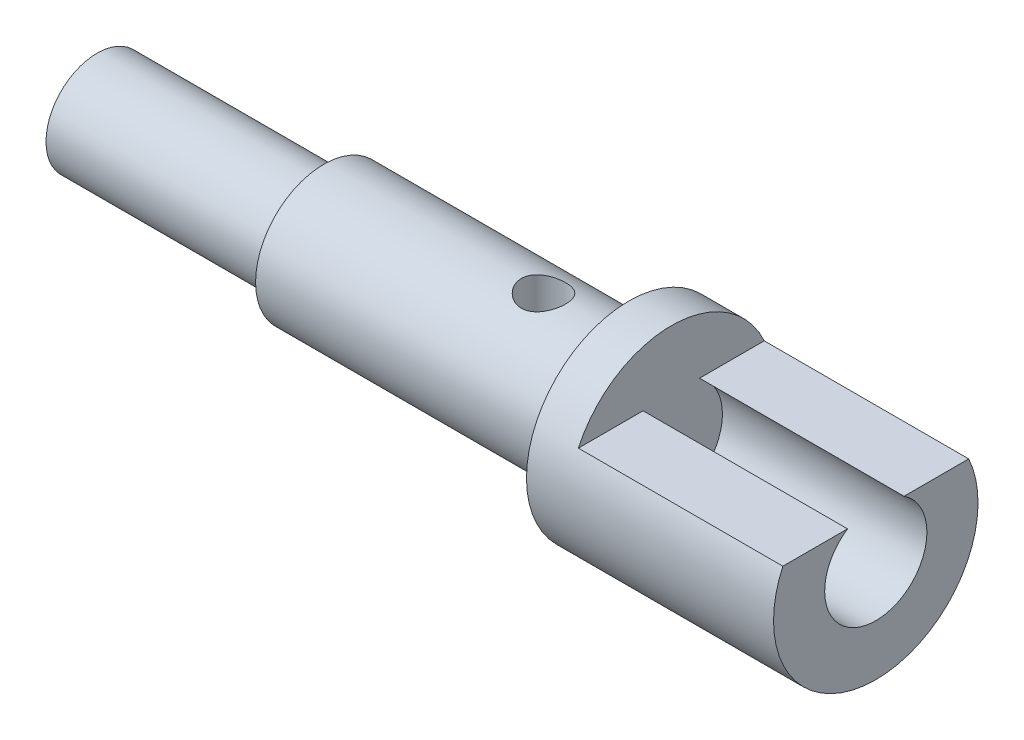
SolidWorks part; units mm, degrees
material "6063-O"
ref_plane "正面" through (0, 0, 0) normal (0, 0, 1) x (1, 0, 0)
ref_plane "平面" through (0, 0, 0) normal (0, 1, 0) x (1, 0, 0)
ref_plane "右側面" through (0, 0, 0) normal (1, 0, 0) x (0, 0, -1)
sketch "ｽｹｯﾁ1" plane through (0, 0, 0) normal (1, 0, 0) x (0, 0, -1)
  circle A0 centre (0, 0) radius 6
  dimension "D1" = 12
extrude "ﾎﾞｽ - 押し出し1" add sketch "ｽｹｯﾁ1" along normal blind 45.7
sketch "ｽｹｯﾁ2" plane through (45.7, 0, 0) normal (1, 0, 0) x (0, 0, -1)
  line L0 (-5.4544, 2.5) -> (5.4544, 2.5)
  circle A0 centre (0, 0) radius 3
  circle A1 centre (0, 0) radius 6 construction
  circle A2 centre (0, 0) radius 6
  circle M2 centre (0, 0) radius 6
  dimension "D1" = 6
  dimension "D2" = 12
  dimension "D3" = 2.5
extrude "ｶｯﾄ - 押し出し1" cut sketch "ｽｹｯﾁ2" against normal blind 12 contours L0 A0 | L0 A0 | A0 L0 M2
sketch "ｽｹｯﾁ3" plane through (0, 0, 0) normal (-1, 0, 0) x (0, 0, 1)
  circle A0 centre (0, 0) radius 4
  dimension "D1" = 8
extrude "ｶｯﾄ - 押し出し2" cut sketch "ｽｹｯﾁ3" against normal blind 31.2 flip side to cut
sketch "ｽｹｯﾁ4" plane through (0, 0, 0) normal (-1, 0, 0) x (0, 0, 1)
  circle A0 centre (0, 0) radius 3
  dimension "D1" = 6
extrude "ｶｯﾄ - 押し出し3" cut sketch "ｽｹｯﾁ4" against normal blind 13.3 flip side to cut
sketch "ｽｹｯﾁ5" plane through (0, 0, 0) normal (0, 1, 0) x (1, 0, 0)
  line L0 (0, 0) -> (45.7, 0) construction
  line L1 (45.7, -3) -> (45.7, 3) construction
  line L2 (45.7, -5.4544) -> (45.7, -1.6583) construction
  circle A0 centre (26.2, 0) radius 1.3
  dimension "D1" = 19.5
  dimension "D2" = 2.6
extrude "ｶｯﾄ - 押し出し4" cut sketch "ｽｹｯﾁ5" against normal through all both and the other way through all
